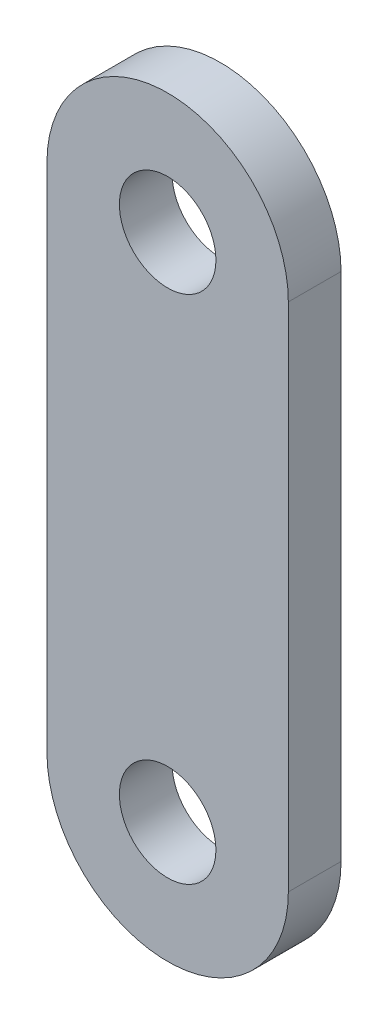
SolidWorks part; units mm, degrees
material "ABS"
ref_plane "前视基准面" through (0, 0, 0) normal (0, 0, 1) x (1, 0, 0)
ref_plane "上视基准面" through (0, 0, 0) normal (0, 1, 0) x (1, 0, 0)
ref_plane "右视基准面" through (0, 0, 0) normal (1, 0, 0) x (0, 0, -1)
sketch "草图1" plane through (0, 0, 0) normal (0, 0, 1) x (1, 0, 0)
  line L0 (0, -6.35) -> (0, 6.35) construction
  line L1 (-3, -6.35) -> (-3, 6.35)
  line L2 (3, -6.35) -> (3, 6.35)
  arc A0 (-3, -6.35) -> (3, -6.35) centre (0, -6.35) ccw
  arc A1 (3, 6.35) -> (-3, 6.35) centre (0, 6.35) ccw
  circle A2 centre (0, 6.35) radius 1.2
  circle A3 centre (0, -6.35) radius 1.2
  point P2 (0, 0)
  dimension "D2" = 2.4
  dimension "D3" = 3
  dimension "D1" = 12.7
extrude "凸台-拉伸1" add sketch "草图1" along normal blind 1.31
